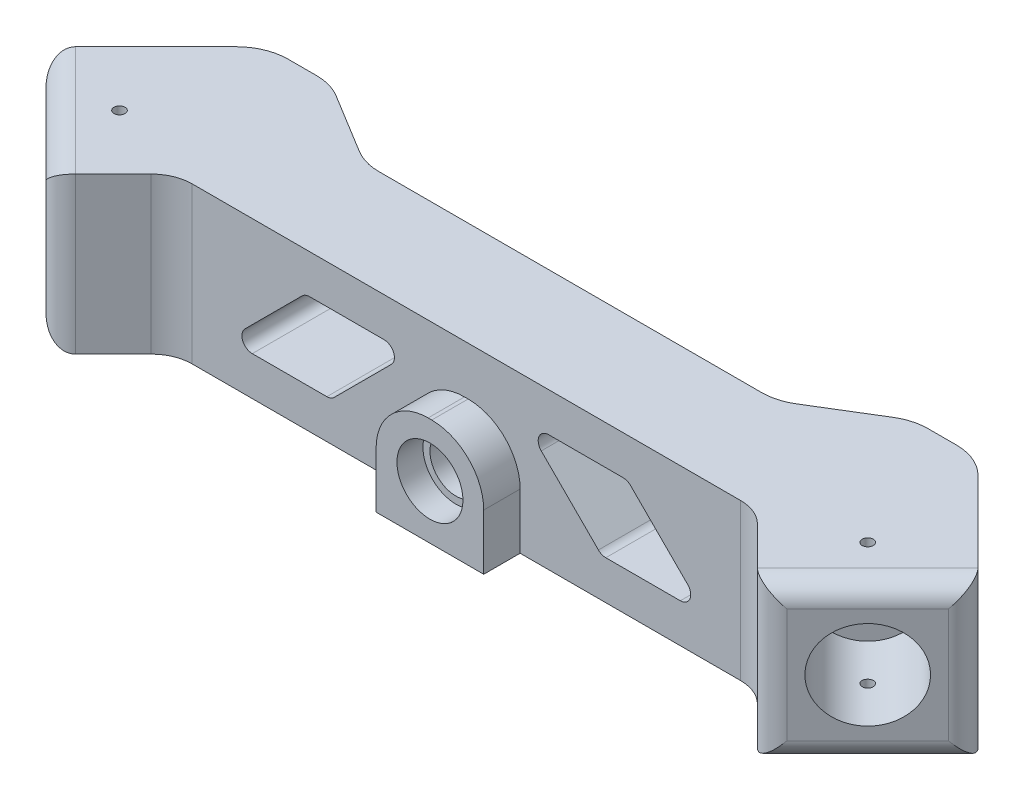
SolidWorks part; units mm, degrees
ref_plane "Front Plane" through (0, 0, 0) normal (0, 0, 1) x (1, 0, 0)
ref_plane "Top Plane" through (0, 0, 0) normal (0, 1, 0) x (1, 0, 0)
ref_plane "Right Plane" through (0, 0, 0) normal (1, 0, 0) x (0, 0, -1)
sketch "Sketch1" plane through (0, 0, 0) normal (0, 1, 0) x (1, 0, 0)
  line L0 (-15.7815, 38.1) -> (0, 38.1)
  line L1 (0, 0) -> (142.24, 0)
  line L5 (0, 0) -> (-15.7815, -15.7815)
  line L6 (-42.7223, 11.1592) -> (-15.7815, -15.7815)
  line L7 (158.0215, 38.1) -> (142.24, 38.1)
  line L8 (142.24, 0) -> (158.0215, -15.7815)
  line L9 (184.9623, 11.1592) -> (158.0215, -15.7815)
  line L10 (158.0215, 38.1) -> (184.9623, 11.1592)
  line L11 (-15.7815, 38.1) -> (-42.7223, 11.1592)
  line L12 (0, 38.1) -> (20.7919, 25.4)
  line L13 (20.7919, 25.4) -> (121.4481, 25.4)
  line L14 (121.4481, 25.4) -> (142.24, 38.1)
  point P5 (71.12, 25.4)
  point P13 (71.12, 0)
  point P15 (3.7746, 34.8671)
  dimension "D2" = 142.24
  dimension "D3" = 38.1
  dimension "D4" = 90
  dimension "D5" = 38.1
  dimension "D6" = 90
  dimension "D7" = 135
  dimension "D8" = 38.1
  dimension "D9" = 90
  dimension "D10" = 90
  dimension "D11" = 38.1
  dimension "D12" = 22.3185
  dimension "D13" = 135
  dimension "D14" = 25.4
  dimension "D15" = 38.1
extrude "Boss-Extrude1" add sketch "Sketch1" along normal blind 38.1
sketch "Sketch2" plane through (-15.7815, 0, 15.7815) normal (-0.7071, 0, 0.7071) x (0.7071, 0, 0.7071)
  line L0 (-38.1, 38.1) -> (0, 0) construction
  line L1 (-38.1, 0) -> (0, 38.1) construction
  circle A0 centre (-19.05, 19.05) radius 10.8585
  dimension "D1" = 21.717
extrude "Cut-Extrude1" cut sketch "Sketch2" against normal blind 25.4
sketch "Sketch3" plane through (86.9015, 0, 86.9015) normal (0.7071, 0, 0.7071) x (0.7071, 0, -0.7071)
  line L0 (100.5789, 38.1) -> (138.6789, 0) construction
  line L1 (100.5789, 0) -> (138.6789, 38.1) construction
  circle A0 centre (119.6289, 19.05) radius 10.8585
  point P11 (119.6289, 19.05)
  dimension "D1" = 21.717
extrude "Cut-Extrude2" cut sketch "Sketch3" against normal blind 25.4
fillet "Fillet1" radius 10 2 edges at (142.24, 19.05, 0) (0, 19.05, 0)
sketch "Sketch5" plane through (0, 0, 0) normal (0, 0, 1) x (1, 0, 0)
  line L0 (4.1421, 0) -> (138.0979, 0) construction
  line L1 (57.9755, 0) -> (84.2645, 0)
  line L2 (57.9755, 0) -> (57.9755, 26.289)
  line L3 (57.9755, 26.289) -> (84.2645, 26.289)
  line L4 (84.2645, 0) -> (84.2645, 26.289)
  line L5 (4.1421, 38.1) -> (138.0979, 38.1) construction
  point P8 (71.12, 38.1)
  point P9 (71.12, 26.289)
  dimension "D1" = 26.289
  dimension "D2" = 26.289
extrude "Boss-Extrude2" add sketch "Sketch5" along normal blind 8.89
sketch "Sketch6" plane through (0, 0, 8.89) normal (0, 0, 1) x (1, 0, 0)
  line L0 (84.2645, 26.289) -> (57.9755, 26.289) construction
  line L1 (57.9755, 26.289) -> (57.9755, 0) construction
  circle A0 centre (71.12, 13.1445) radius 8.0645
  point P4 (71.12, 26.289)
  point P7 (57.9755, 13.1445)
  dimension "D1" = 16.129
extrude "Cut-Extrude3" cut sketch "Sketch6" against normal blind 6.35
sketch "Sketch7" plane through (0, 0, 2.54) normal (0, 0, 1) x (1, 0, 0)
  circle A0 centre (71.12, 13.1445) radius 6.35
  circle A1 centre (71.12, 13.1445) radius 8.0645 construction
  circle A2 centre (71.12, 13.1445) radius 8.0645 construction
  dimension "D1" = 12.7
extrude "Cut-Extrude4" cut sketch "Sketch7" against normal blind 5.08
fillet "Fillet3" radius 12.7 2 edges at (84.2645, 26.289, 4.445) (57.9755, 26.289, 4.445)
fillet "Fillet4" radius 5.08 8 edges at (171.4919, 0, 2.3112) (184.9623, 19.05, -11.1592) (171.4919, 38.1, 2.3112) (158.0215, 19.05, 15.7815) (-29.2519, 0, 2.3112) (-15.7815, 19.05, 15.7815) (-29.2519, 38.1, 2.3112) (-42.7223, 19.05, -11.1592)
fillet "Fillet5" radius 12.7 6 edges at (20.7919, 19.05, -25.4) (121.4481, 19.05, -25.4) (158.0215, 19.05, -38.1) (142.24, 19.05, -38.1) (0, 19.05, -38.1) (-15.7815, 19.05, -38.1)
sketch "Sketch8" plane through (0, 38.1, 0) normal (0, 1, 0) x (1, 0, 0)
  line L0 (71.12, 0) -> (71.12, 21.2039) construction
  line L1 (4.1421, 0) -> (138.0979, 0) construction
  line L2 (-19.3736, -12.1894) -> (-39.1302, 7.5671) construction
  line L3 (-19.3736, -12.1894) -> (-39.1302, 7.5671) construction
  line L4 (-29.2519, -2.3112) -> (-20.2717, 6.6691) construction
  circle A0 centre (-20.2717, 6.6691) radius 1.35
  circle A1 centre (162.5117, 6.6691) radius 1.35
  dimension "D2" = 2.7
  dimension "D1" = 12.7
extrude "Cut-Extrude5" cut sketch "Sketch8" against normal through all both and the other way through all
sketch "Sketch9" plane through (0, 0, 0) normal (0, 0, 1) x (1, 0, 0)
  line L0 (12.7, 9.525) -> (38.1, 9.525)
  line L1 (38.1, 9.525) -> (57.15, 28.575)
  line L2 (57.15, 28.575) -> (31.75, 28.575)
  line L3 (31.75, 28.575) -> (12.7, 9.525)
  line L4 (71.12, 38.1) -> (71.12, 31.3797) construction
  line L5 (4.1421, 38.1) -> (138.0979, 38.1) construction
  line L6 (4.1421, 0) -> (57.9755, 0) construction
  line L7 (85.09, 28.575) -> (110.49, 28.575)
  line L8 (104.14, 9.525) -> (85.09, 28.575)
  line L9 (129.54, 9.525) -> (104.14, 9.525)
  line L10 (110.49, 28.575) -> (129.54, 9.525)
  dimension "D1" = 45
  dimension "D2" = 19.05
  dimension "D3" = 25.4
  dimension "D4" = 13.97
  dimension "D5" = 9.525
extrude "Cut-Extrude6" cut sketch "Sketch9" against normal through all both and the other way through all
fillet "Fillet6" radius 2.54 8 edges at (129.54, 9.525, -15.1713) (110.49, 28.575, -12.7) (85.09, 28.575, -12.7) (104.14, 9.525, -12.7) (38.1, 9.525, -12.7) (57.15, 28.575, -12.7) (31.75, 28.575, -12.7) (12.7, 9.525, -15.1713)
